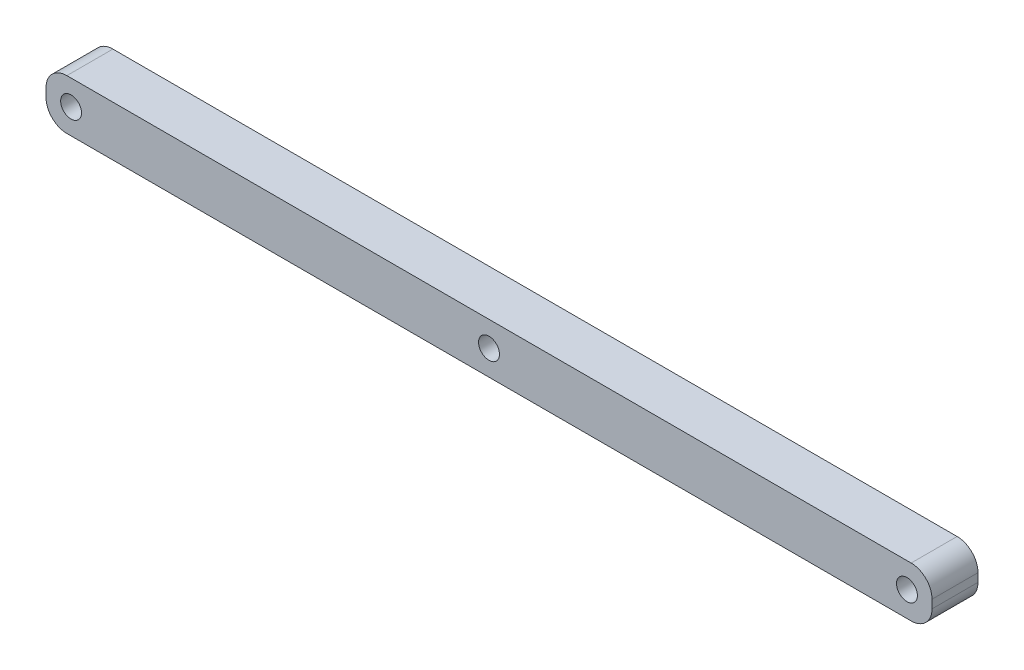
SolidWorks part; units mm, degrees
ref_plane "Front Plane" through (0, 0, 0) normal (0, 0, 1) x (1, 0, 0)
ref_plane "Top Plane" through (0, 0, 0) normal (0, 1, 0) x (1, 0, 0)
ref_plane "Right Plane" through (0, 0, 0) normal (1, 0, 0) x (0, 0, -1)
sketch "Sketch1" plane through (0, 0, 0) normal (0, 0, 1) x (1, 0, 0)
  line L1 (0, 0) -> (424, 0)
  line L2 (0, 0) -> (0, 24)
  line L3 (0, 24) -> (424, 24)
  line L4 (424, 0) -> (424, 24)
  circle A0 centre (12, 12) radius 5
  circle A1 centre (412, 12) radius 5
  circle A2 centre (212, 12) radius 5
  dimension "D5" = 10
  dimension "D6" = 10
  dimension "D8" = 12
  dimension "D9" = 10
  dimension "D1" = 400
  dimension "D2" = 12
  dimension "D3" = 12
  dimension "D4" = 424
  dimension "D7" = 12
  dimension "D10" = 12
  dimension "D11" = 200
extrude "Boss-Extrude1" add sketch "Sketch1" along normal blind 22
fillet "Fillet1" radius 10 4 edges at (424, 24, 11) (424, 0, 11) (0, 24, 11) (0, 0, 11)
